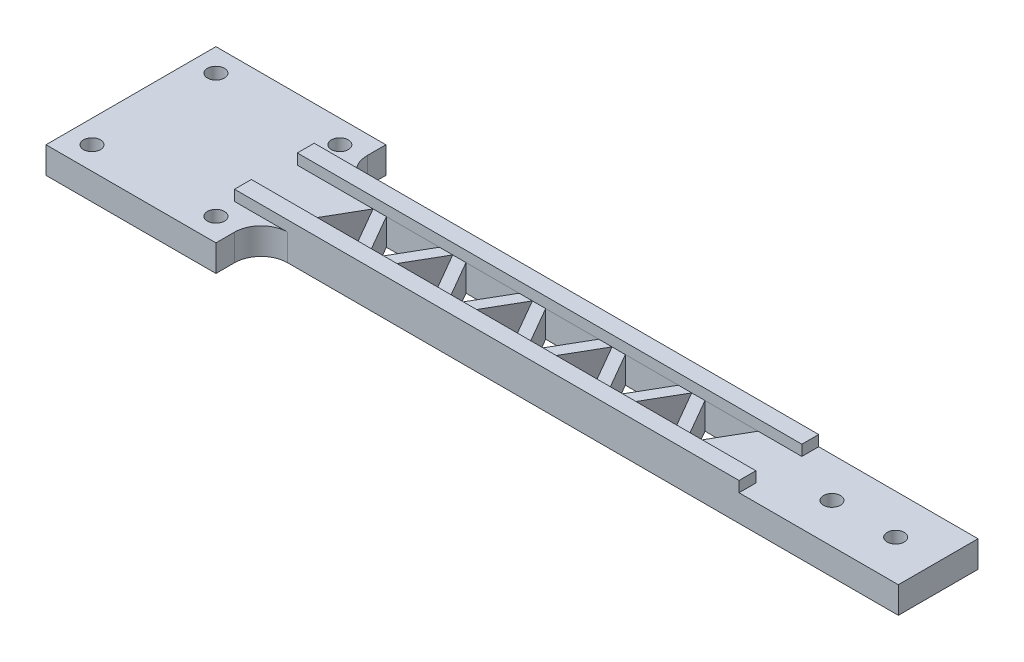
SolidWorks part; units mm, degrees
ref_plane "Спереди" through (0, 0, 0) normal (0, 0, 1) x (1, 0, 0)
ref_plane "Сверху" through (0, 0, 0) normal (0, 1, 0) x (1, 0, 0)
ref_plane "Справа" through (0, 0, 0) normal (1, 0, 0) x (0, 0, -1)
other "Configuration Table"
sketch "Эскиз1" plane through (0, 0, 0) normal (0, 1, 0) x (1, 0, 0)
  line L1 (-66.6116, 14.0496) -> (53.3884, 14.0496)
  line L2 (-66.6116, 14.0496) -> (-66.6116, -0.9504)
  line L3 (-66.6116, -0.9504) -> (53.3884, -0.9504)
  line L4 (53.3884, 14.0496) -> (53.3884, -0.9504)
  dimension "D1" = 120
  dimension "D2" = 15
extrude "Бобышка-Вытянуть1" add sketch "Эскиз1" along normal blind 5
sketch "Эскиз2" plane through (0, 5, 0) normal (0, 1, 0) x (1, 0, 0)
  line L0 (53.3884, -0.9504) -> (53.3884, 14.0496) construction
  line L1 (53.3884, 14.0496) -> (-66.6116, 14.0496) construction
  line L2 (-66.6116, -0.9504) -> (53.3884, -0.9504) construction
  circle A0 centre (45.3884, 6.5496) radius 1.6
  circle A1 centre (33.3884, 6.5496) radius 1.6
  dimension "D3" = 3.2
  dimension "D4" = 3.2
  dimension "D1" = 8
  dimension "D2" = 20
  dimension "D5" = 7.5
  dimension "D6" = 7.5
extrude "Вырез-Вытянуть1" cut sketch "Эскиз2" against normal blind 10
sketch "Эскиз3" plane through (0, 5, 0) normal (0, 1, 0) x (1, 0, 0)
  line L1 (-66.6116, 22.5496) -> (-98.6116, 22.5496)
  line L2 (-66.6116, 22.5496) -> (-66.6116, -9.4504)
  line L3 (-66.6116, -9.4504) -> (-98.6116, -9.4504)
  line L4 (-98.6116, 22.5496) -> (-98.6116, -9.4504)
  line L5 (-66.6116, 14.0496) -> (-66.6116, -0.9504) construction
  dimension "D1" = 32
  dimension "D2" = 8.5
  dimension "D3" = 8.5
extrude "Бобышка-Вытянуть2" add sketch "Эскиз3" against normal blind 5
sketch "Эскиз4" plane through (0, 5, 0) normal (0, 1, 0) x (1, 0, 0)
  line L0 (-98.6116, -9.4504) -> (-66.6116, 22.5496)
  line L1 (-98.6116, 22.5496) -> (-66.6116, -9.4504)
  circle A0 centre (-70.9443, 18.2168) radius 1.6
  circle A1 centre (-94.2788, -5.1177) radius 1.6
  circle A2 centre (-70.9461, -5.1158) radius 1.6
  circle A3 centre (-94.2807, 18.2187) radius 1.6
  point P16 (-82.6116, 6.5496)
  point P20 (-82.6134, 6.5496)
  dimension "D1" = 3.2
  dimension "D2" = 3.2
  dimension "D7" = 3.2
  dimension "D12" = 3.2
  dimension "D3" = 33
  dimension "D4" = 16.5
  dimension "D5" = 6.1274
  dimension "D6" = 6.1274
  dimension "D8" = 33
  dimension "D10" = 6.13
  dimension "D11" = 6.1248
extrude "Вырез-Вытянуть2" cut sketch "Эскиз4" against normal blind 7.5 contours L1 A3 | L0 A0 | L1 A3 | L0 A1 | L0 A1 | L1 A2 | L1 A2
fillet "Скругление2" radius 5 1 edges at (-66.6116, 2.5, 0.9504)
fillet "Скругление4" radius 5 1 edges at (-66.6116, 2.5, -14.0496)
sketch "Эскиз6" plane through (0, 5, 0) normal (0, 1, 0) x (1, 0, 0)
  line L0 (-62.3517, 2.2196) -> (-57.3517, 10.8798)
  line L1 (-57.3517, 10.8798) -> (-52.3517, 2.2196)
  line L2 (-52.3517, 2.2196) -> (-62.3517, 2.2196)
  line L3 (-61.6116, -0.9504) -> (53.3884, -0.9504) construction
  line L4 (-47.3517, 2.2196) -> (-42.3517, 10.8798)
  line L5 (-37.3517, 2.2196) -> (-47.3517, 2.2196)
  line L6 (-42.3517, 10.8798) -> (-37.3517, 2.2196)
  line L7 (-32.3517, 2.2196) -> (-27.3517, 10.8798)
  line L8 (-22.3517, 2.2196) -> (-32.3517, 2.2196)
  line L9 (-27.3517, 10.8798) -> (-22.3517, 2.2196)
  line L10 (-17.3517, 2.2196) -> (-12.3517, 10.8798)
  line L11 (-7.3517, 2.2196) -> (-17.3517, 2.2196)
  line L12 (-12.3517, 10.8798) -> (-7.3517, 2.2196)
  line L13 (-2.3517, 2.2196) -> (2.6483, 10.8798)
  line L14 (7.6483, 2.2196) -> (-2.3517, 2.2196)
  line L15 (2.6483, 10.8798) -> (7.6483, 2.2196)
  line L25 (-62.3517, 2.2196) -> (-47.3517, 2.2196) construction
  line L26 (-54.8517, 10.8798) -> (-49.8517, 2.2196)
  line L27 (-49.8517, 2.2196) -> (-44.8517, 10.8798)
  line L28 (-44.8517, 10.8798) -> (-54.8517, 10.8798)
  line L29 (53.3884, 14.0496) -> (-61.6116, 14.0496) construction
  line L30 (-39.8517, 10.8798) -> (-34.8517, 2.2196)
  line L31 (-29.8517, 10.8798) -> (-39.8517, 10.8798)
  line L32 (-34.8517, 2.2196) -> (-29.8517, 10.8798)
  line L33 (-24.8517, 10.8798) -> (-19.8517, 2.2196)
  line L34 (-14.8517, 10.8798) -> (-24.8517, 10.8798)
  line L35 (-19.8517, 2.2196) -> (-14.8517, 10.8798)
  line L36 (-9.8517, 10.8798) -> (-4.8517, 2.2196)
  line L37 (0.1483, 10.8798) -> (-9.8517, 10.8798)
  line L38 (-4.8517, 2.2196) -> (0.1483, 10.8798)
  line L39 (5.1483, 10.8798) -> (10.1483, 2.2196)
  line L40 (15.1483, 10.8798) -> (5.1483, 10.8798)
  line L41 (10.1483, 2.2196) -> (15.1483, 10.8798)
  line L48 (-54.8517, 10.8798) -> (-39.8517, 10.8798) construction
  line L49 (42.6483, 2.2196) -> (47.6483, 10.8798) [skipped]
  line L50 (47.6483, 10.8798) -> (52.6483, 2.2196) [skipped]
  line L51 (52.6483, 2.2196) -> (42.6483, 2.2196) [skipped]
  line L52 (40.1483, 2.2196) -> (45.1483, 10.8798) [skipped]
  line L53 (35.1483, 10.8798) -> (40.1483, 2.2196) [skipped]
  line L54 (45.1483, 10.8798) -> (35.1483, 10.8798) [skipped]
  line L55 (27.6483, 2.2196) -> (32.6483, 10.8798) [skipped]
  line L56 (32.6483, 10.8798) -> (37.6483, 2.2196) [skipped]
  line L57 (37.6483, 2.2196) -> (27.6483, 2.2196) [skipped]
  line L58 (20.1483, 10.8798) -> (25.1483, 2.2196) [skipped]
  line L59 (25.1483, 2.2196) -> (30.1483, 10.8798) [skipped]
  line L60 (30.1483, 10.8798) -> (20.1483, 10.8798) [skipped]
  line L61 (12.6483, 2.2196) -> (17.6483, 10.8798) [skipped]
  line L62 (17.6483, 10.8798) -> (22.6483, 2.2196) [skipped]
  line L63 (22.6483, 2.2196) -> (12.6483, 2.2196) [skipped]
  dimension "D1" = 10
  dimension "D2" = 3.17
  dimension "D4" = 15
  dimension "D5" = 3.17
  dimension "D6" = 3.1697
  dimension "D7" = 2.5
  dimension "D8" = 2.5
  dimension "D10" = 15
  dimension "D3" = 8
  dimension "D9" = 7
extrude "Вырез-Вытянуть3" cut sketch "Эскиз6" against normal blind 10
sketch3d "Трехмерный эскиз1" plane through (0, 0, 0) normal (0, 0, 1) x (1, 0, 0)
  dimension "D1" = 30
sketch "Эскиз12" plane through (23.3884, 0, 0) normal (1, 0, 0) x (0, 0, -1)
  line L1 (-0.9504, 5) -> (2.2196, 5)
  line L2 (-0.9504, 5) -> (-0.9504, 7)
  line L3 (-0.9504, 7) -> (2.2196, 7)
  line L4 (2.2196, 5) -> (2.2196, 7)
  line L5 (10.8796, 5) -> (14.0496, 5)
  line L6 (10.8796, 5) -> (10.8796, 7)
  line L7 (10.8796, 7) -> (14.0496, 7)
  line L8 (14.0496, 5) -> (14.0496, 7)
  dimension "D1" = 3.17
  dimension "D2" = 2
extrude "Бобышка-Вытянуть4" add sketch "Эскиз12" against normal blind 95
sketch "Эскиз13" plane through (0, 5, 0) normal (0, 1, 0) x (1, 0, 0)
  line L0 (28.3884, -0.9504) -> (20.5401, 6.2013)
  line L1 (20.5401, 6.2013) -> (27.6918, 14.0496)
  line L2 (53.3884, 14.0496) -> (23.3884, 14.0496) construction
  line L3 (23.3884, -0.9504) -> (53.3884, -0.9504) construction
  dimension "D1" = 90
  dimension "D2" = 25
